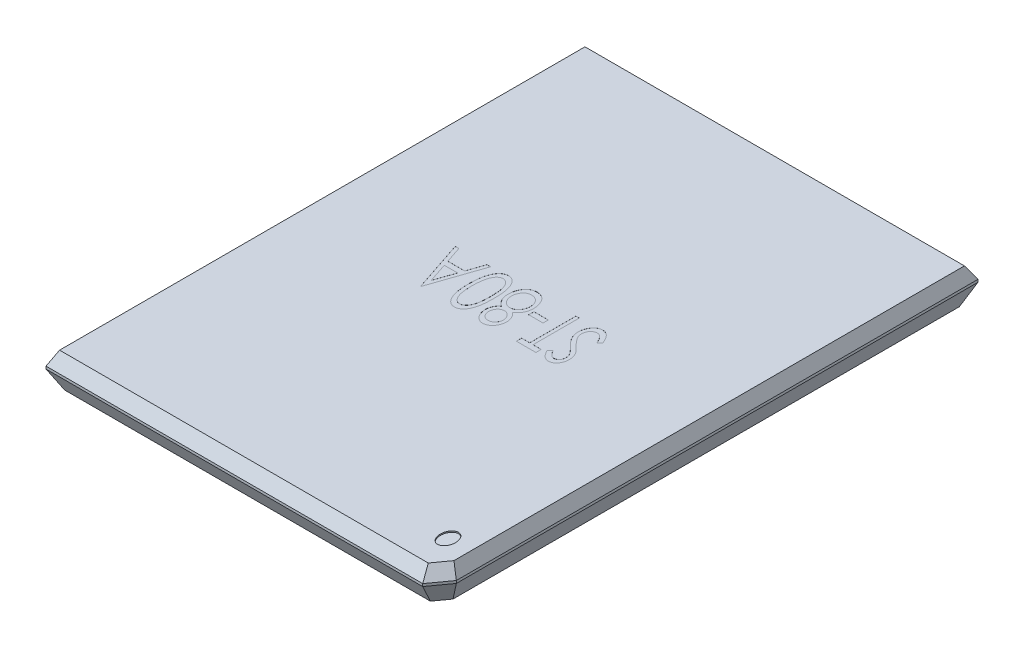
SolidWorks part; units mm, degrees
ref_plane "Front Plane" through (0, 0, 0) normal (0, 0, 1) x (1, 0, 0)
ref_plane "Top Plane" through (0, 0, 0) normal (0, 1, 0) x (1, 0, 0)
ref_plane "Right Plane" through (0, 0, 0) normal (1, 0, 0) x (0, 0, -1)
sketch "Sketch1" plane through (0, 0, 0) normal (0, 1, 0) x (1, 0, 0)
  line L0 (6.0007, -5.5678) -> (5.5678, -6.0007)
  line L1 (5.2085, -6.0007) -> (5.5678, -6.0007)
  line L2 (-6.0007, -6.0007) -> (5.2085, -6.0007)
  line L3 (-6.0007, 6.0007) -> (-6.0007, -6.0007)
  line L4 (-6.0007, 6.0007) -> (6.0007, 6.0007)
  line L5 (6.0007, 6.0007) -> (6.0007, -5.2085)
  line L6 (6.0007, -5.2085) -> (6.0007, -5.5678)
extrude "Extrude1" add sketch "Sketch1" along normal blind 1.397
chamfer "Chamfer1" distance 0.508 angle 19 5 edges at (5.7843, 1.397, 5.7843) (-0.2165, 1.397, 6.0007) (-6.0007, 1.397, 0) (0, 1.397, -6.0007) (6.0007, 1.397, -0.2165)
sketch "Sketch2" plane through (0, 1.397, 0) normal (0, 1, 0) x (-1, 0, 0)
  circle A0 centre (-5.1413, 5.1331) radius 0.2316
extrude "Cut-Extrude1" cut sketch "Sketch2" against normal blind 0.0508
sketch "Sketch3" plane through (0, 1.397, 0) normal (0, 1, 0) x (-1, 0, 0)
  text T0 "ST-80A" font "Century Gothic" height 1.143
extrude "Cut-Extrude2" cut sketch "Sketch3" against normal blind 0.0025
chamfer "Chamfer2" distance 0.7874 angle 17 5 edges at (-6.0007, 0, 0) (-0.2165, 0, 6.0007) (5.7843, 0, 5.7843) (6.0007, 0, -0.2165) (0, 0, -6.0007)
scale "Scale1" bodies to scale 103 scale about centroid uniform scaling no x scale factor 1.3 y scale factor 1 z scale factor 1.8
